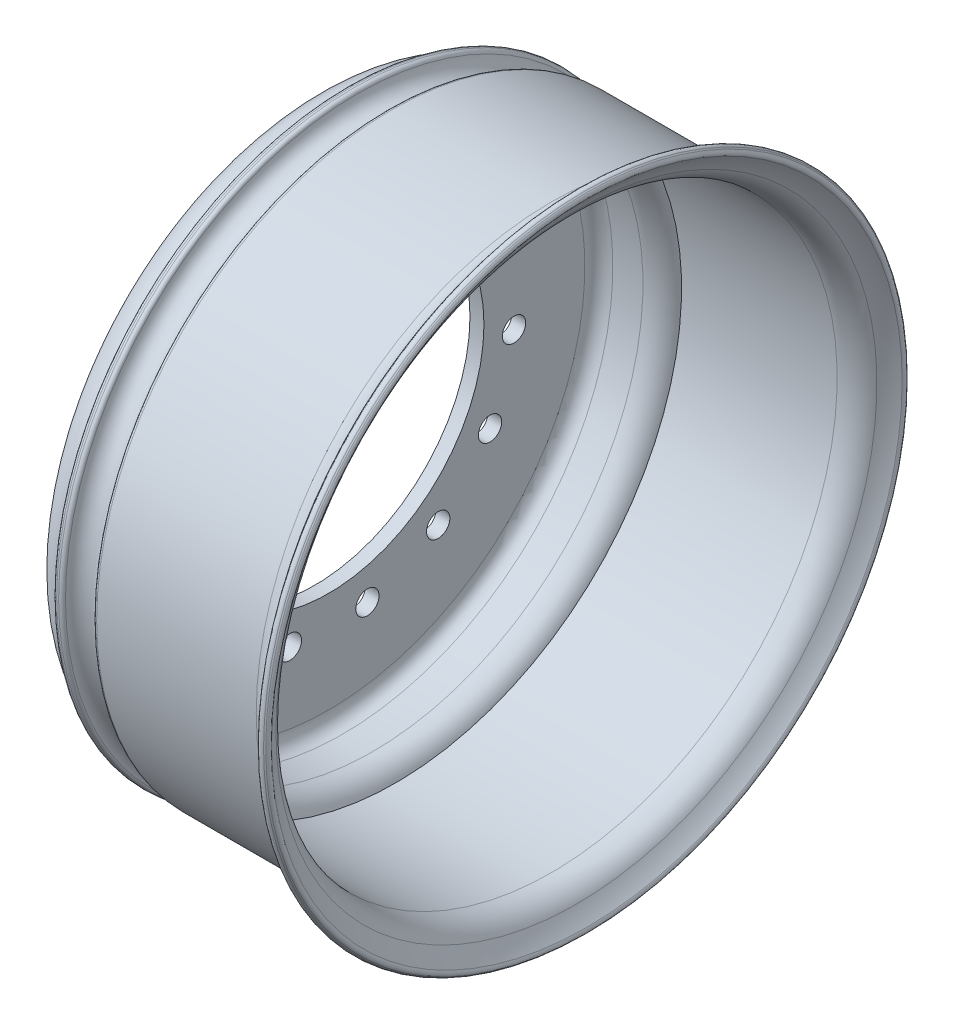
SolidWorks part; units mm, degrees
ref_plane "Front Plane" through (0, 0, 0) normal (0, 0, 1) x (1, 0, 0)
ref_plane "Top Plane" through (0, 0, 0) normal (0, 1, 0) x (1, 0, 0)
ref_plane "Right Plane" through (0, 0, 0) normal (1, 0, 0) x (0, 0, -1)
sketch "Sketch1" plane through (0, 0, 0) normal (0, 0, 1) x (1, 0, 0)
  line L0 (0, 0) -> (315.4234, 0) construction
  line L1 (0, 190) -> (6, 190)
  line L2 (26, 190) -> (131, 190)
  line L3 (0, 184) -> (1.1676, 184)
  line L4 (30.8324, 184) -> (131, 184)
  line L6 (155.3992, 204.8238) -> (151, 208.9038)
  line L7 (16, 174) -> (-3.3875, 174)
  line L8 (-12.3875, 165) -> (-12.3875, 100)
  line L9 (-12.3875, 100) -> (-21.3875, 100)
  line L10 (-21.3875, 100) -> (-21.3875, 165)
  line L11 (-3.3875, 183) -> (1.6125, 183)
  line L12 (0, 184) -> (0, 190)
  arc A0 (6, 190) -> (26, 190) centre (16, 190) ccw
  arc A1 (131, 190) -> (141.9127, 196.4038) centre (131, 202.5) ccw
  arc A2 (141.9127, 196.4038) -> (151, 208.9038) centre (198.6585, 164.7035) cw
  arc A3 (1.1676, 184) -> (1.6125, 183) centre (16, 190) ccw
  arc A4 (131, 184) -> (147.1507, 193.4776) centre (131, 202.5) ccw
  arc A5 (147.1507, 193.4776) -> (155.3992, 204.8238) centre (198.6585, 164.7035) cw
  arc A6 (-3.3875, 174) -> (-12.3875, 165) centre (-3.3875, 165) ccw
  arc A7 (-21.3875, 165) -> (-3.3875, 183) centre (-3.3875, 165) cw
  arc A8 (16, 174) -> (30.8324, 184) centre (16, 190) ccw
  arc A10 (1.1676, 184) -> (30.8324, 184) centre (16, 190) ccw construction
  dimension "D2" = 10
  dimension "D4" = 12.5
  dimension "D5" = 65
  dimension "D11" = 9
  dimension "D12" = 18
  dimension "D1" = 105
  dimension "D3" = 6
  dimension "D6" = 190
  dimension "D7" = 12.5
  dimension "D8" = 145
  dimension "D10" = 9
  dimension "D13" = 9
  dimension "D14" = 5
  dimension "D15" = 65
  dimension "D9" = 6
revolve "Revolve2" add sketch "Sketch1" angle 360 about L0
sketch "Sketch3" plane through (-21.3875, 0, 0) normal (-1, 0, 0) x (0, 0, 1)
  circle A0 centre (0, 120) radius 7.5
  point P2 (0, 0)
  point P4 (0, 0)
  dimension "D1" = 15
  dimension "D2" = 120
extrude "Cut-Extrude1" cut sketch "Sketch3" against normal through all
pattern_circular "CirPattern1" count 15 every 24 about axis through (0, 0, 0) along (1, 0, 0) of "Cut-Extrude1"
fillet "Fillet1" radius 2.5 2 edges at (155.3992, 0, 204.8238) (151, 0, 208.9038)
fillet "Fillet2" radius 2.5 3 edges at (6, 0, 190) (0, 0, 190) (26, 0, 190)
